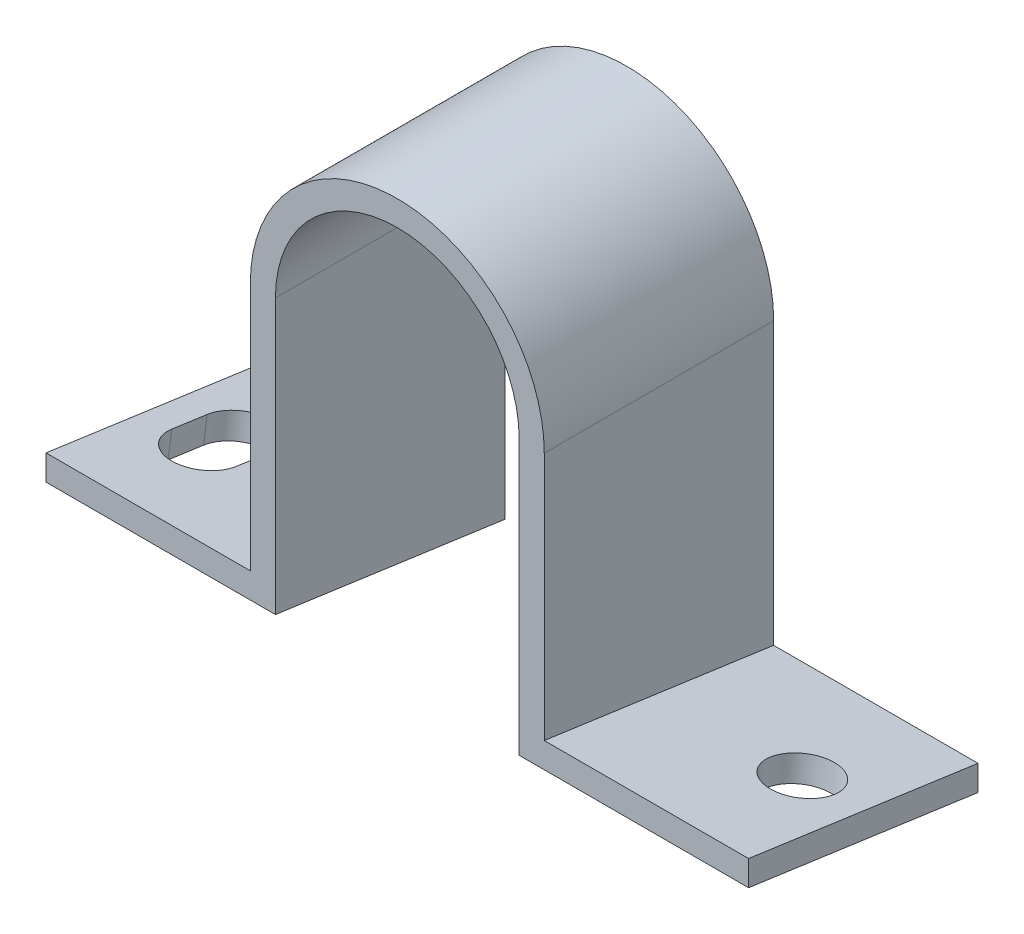
SolidWorks part; units mm, degrees
material "AISI 1010 钢，热轧条材"
ref_plane "前视基准面" through (0, 0, 0) normal (0, 0, 1) x (1, 0, 0)
ref_plane "上视基准面" through (0, 0, 0) normal (0, 1, 0) x (1, 0, 0)
ref_plane "右视基准面" through (0, 0, 0) normal (1, 0, 0) x (0, 0, -1)
sketch "草图1" plane through (0, 0, 0) normal (0, 0, 1) x (1, 0, 0)
  line L0 (-17, 0) -> (-17, -66.8639)
  line L1 (-20.5, 0) -> (-20.5, -66.8639)
  line L2 (-17, -66.8639) -> (-20.5, -66.8639)
  line L3 (0, 4.1737) -> (0, 50004.1737) construction
  line L4 (17, -66.8639) -> (20.5, -66.8639)
  line L5 (20.5, 0) -> (20.5, -66.8639)
  line L6 (17, 0) -> (17, -66.8639)
  arc A0 (17, 0) -> (-17, 0) centre (0, 0) ccw
  arc A1 (20.5, 0) -> (-20.5, 0) centre (0, 0) ccw
  circle A3 centre (0, 0) radius 20.5 construction
  circle A4 centre (0, 0) radius 17 construction
  point P4 (16.2572, 4.9703)
  point P15 (20.5, 0)
  dimension "D1" = 34
  dimension "D2" = 3.5
extrude "凸台-拉伸1" add sketch "草图1" along normal mid plane 32
sketch "草图2" plane through (0, 0, 0) normal (1, 0, 0) x (0, 0, -1)
  line L0 (0, 0) -> (50000, 0) construction
  line L1 (0, 0) -> (0, -50000) construction
  line L2 (29.9617, -44.7108) -> (0, -40.5) construction
  line L3 (16, -42.7487) -> (-16, -38.2513)
  line L4 (16, -66.8639) -> (16, 0) construction
  line L5 (-16, -66.8639) -> (-16, 0) construction
  line L6 (-16, -38.2513) -> (-16, -66.8639)
  line L7 (-16, -66.8639) -> (16, -66.8639)
  line L8 (16, -66.8639) -> (16, -42.7487)
  dimension "D1" = 8
  dimension "D2" = 40.5
extrude "切除-拉伸1" cut sketch "草图2" against normal mid plane 100
sketch "草图3" plane through (-20.5, 0, 0) normal (-1, 0, 0) x (0, 0, 1)
  line L0 (-16, -42.7487) -> (16, -38.2513)
  line L1 (-16, -39.2143) -> (16, -34.717)
  line L4 (-16, -42.7487) -> (-16, -39.2143)
  line L5 (16, -38.2513) -> (16, -34.717)
  line L7 (-16.4871, -39.2827) -> (15.5129, -34.7854) construction
  dimension "D1" = 3.5
extrude "凸台-拉伸2" add sketch "草图3" along normal blind 28.5
mirror "镜向1" about plane through (0, 0, 0) normal (1, 0, 0) of "凸台-拉伸2"
sketch "草图4" plane through (0, -36.2496, 5.0946) normal (0, 0.9903, -0.1392) x (1, 0, 0)
  line L0 (0, 0) -> (0, -50000) construction
  line L1 (-49, 5.1446) -> (49, 5.1446) construction
  line L2 (-49, -11.0126) -> (-49, 21.3019) construction
  line L3 (49, -11.0126) -> (49, 21.3019) construction
  line L4 (-40.5, 21.3019) -> (-40.5, -11.0126) construction
  line L5 (-49, 21.3019) -> (-20.5, 21.3019) construction
  line L6 (-49, -11.0126) -> (-20.5, -11.0126) construction
  line L7 (40.5, 21.3019) -> (40.5, -11.0126) construction
  line L8 (-36, 7.6446) -> (-36, 2.6446)
  line L9 (-45, 7.6446) -> (-45, 2.6446)
  arc A0 (-36, 7.6446) -> (-45, 7.6446) centre (-40.5, 7.6446) ccw
  arc A1 (-45, 2.6446) -> (-36, 2.6446) centre (-40.5, 2.6446) ccw
  circle A2 centre (40.5, 5.1446) radius 4.5
  dimension "D2" = 9
  dimension "D4" = 9
  dimension "D1" = 81
  dimension "D3" = 5
extrude "切除-拉伸2" cut sketch "草图4" against normal blind 28.5
